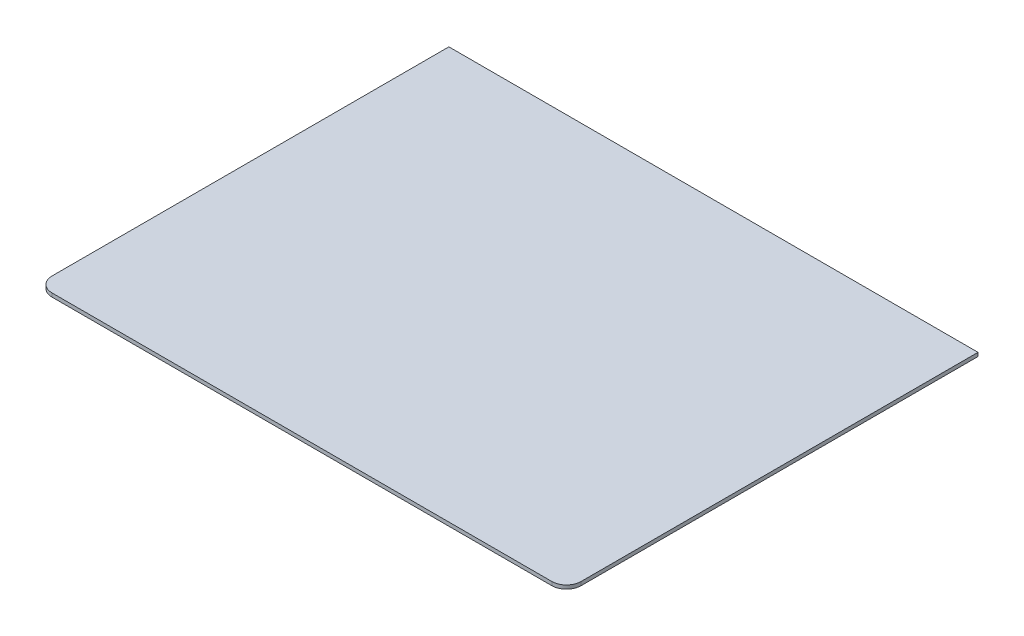
SolidWorks part; units mm, degrees
material "6061-O (SS)"
ref_plane "Front Plane" through (0, 0, 0) normal (0, 0, 1) x (1, 0, 0)
ref_plane "Top Plane" through (0, 0, 0) normal (0, 1, 0) x (1, 0, 0)
ref_plane "Right Plane" through (0, 0, 0) normal (1, 0, 0) x (0, 0, -1)
sketch "Sketch2" plane through (0, 0, 0) normal (0, 1, 0) x (1, 0, 0)
  line L1 (-228.6, -177.8) -> (228.6, -177.8)
  line L2 (-228.6, -177.8) -> (-228.6, 177.8)
  line L3 (-228.6, 177.8) -> (228.6, 177.8)
  line L4 (228.6, -177.8) -> (228.6, 177.8)
  line L5 (-228.6, -177.8) -> (228.6, 177.8) construction
  line L6 (-228.6, 177.8) -> (228.6, -177.8) construction
  point P0 (0, 0)
  dimension "D1" = 355.6
  dimension "D2" = 457.2
extrude "Boss-Extrude1" add sketch "Sketch2" along normal blind 3.175
fillet "Fillet1" radius 12.7 2 edges at (-228.6, 1.5875, 177.8) (228.6, 1.5875, 177.8)
